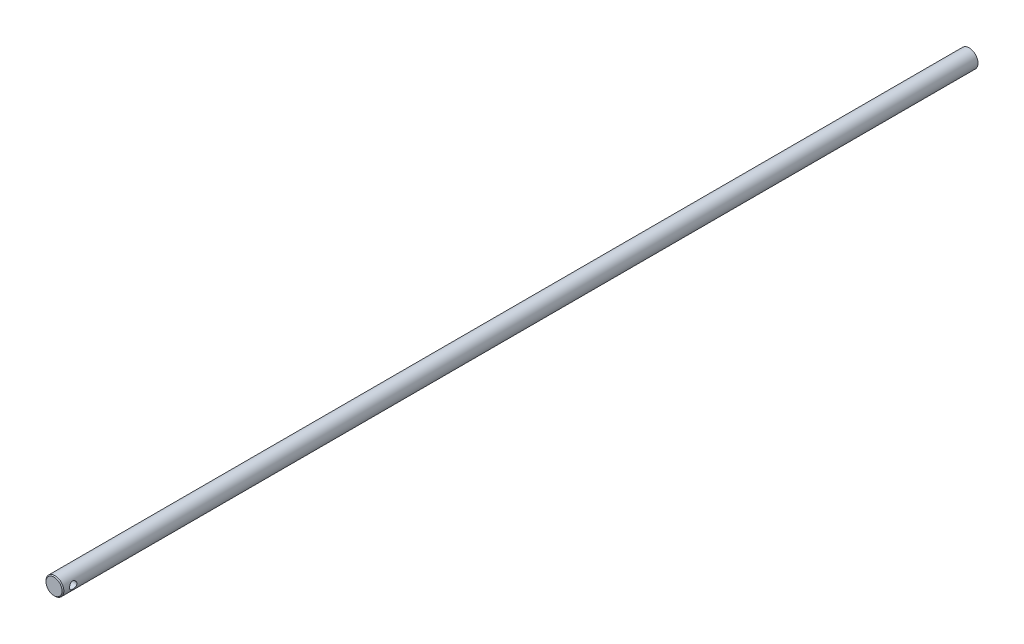
SolidWorks part; units mm, degrees
ref_plane "Спереди" through (0, 0, 0) normal (0, 0, 1) x (1, 0, 0)
ref_plane "Сверху" through (0, 0, 0) normal (0, 1, 0) x (1, 0, 0)
ref_plane "Справа" through (0, 0, 0) normal (1, 0, 0) x (0, 0, -1)
sketch "Эскиз1" plane through (0, 0, 0) normal (0, 0, 1) x (1, 0, 0)
  circle A0 centre (21, 0) radius 10
  dimension "D1" = 20
extrude "Бобышка-Вытянуть1" add sketch "Эскиз1" along normal blind 25.6 and the other way blind 1000
sketch "Эскиз2" plane through (0, 0, 0) normal (1, 0, 0) x (0, 0, -1)
  line L0 (-25.6, 10) -> (-25.6, -10) construction
  line L1 (-25.6, 0) -> (-14, 0) construction
  circle A0 centre (-14, 0) radius 4.1
  dimension "D1" = 8.2
  dimension "D2" = 11.6
extrude "Вырез-Вытянуть1" cut sketch "Эскиз2" against normal through all both and the other way through all
chamfer "Фаска1" distance 1 angle 45 1 edges at (31, 0, 25.6)
